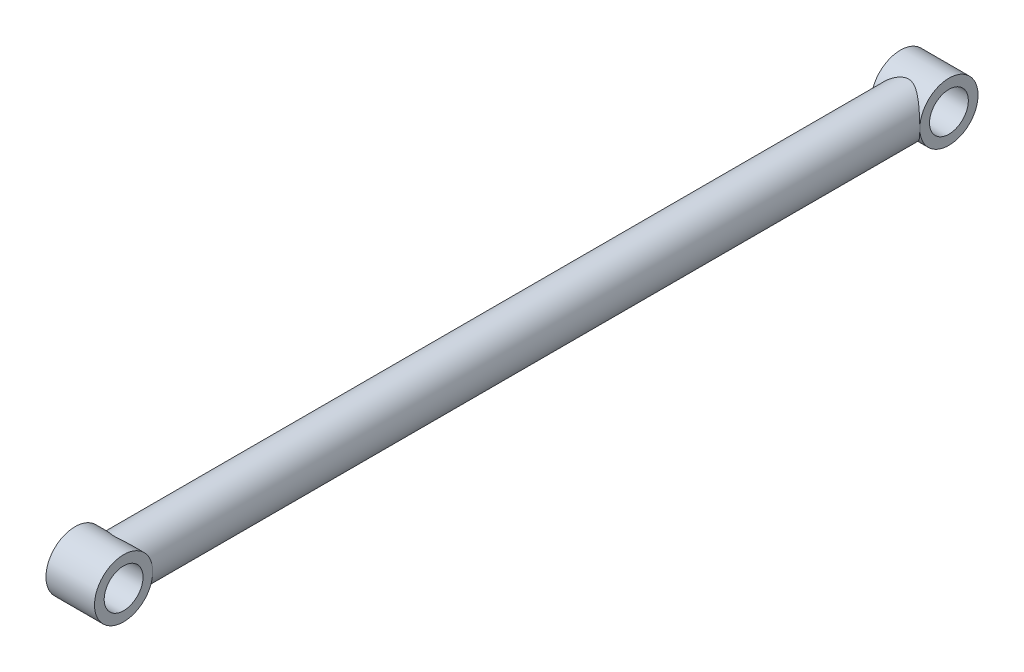
SolidWorks part; units mm, degrees
ref_plane "Front Plane" through (0, 0, 0) normal (0, 0, 1) x (1, 0, 0)
ref_plane "Top Plane" through (0, 0, 0) normal (0, 1, 0) x (1, 0, 0)
ref_plane "Right Plane" through (0, 0, 0) normal (1, 0, 0) x (0, 0, -1)
sketch "Sketch3" plane through (0, 0, 0) normal (0, 0, 1) x (1, 0, 0)
  circle A0 centre (0, 0) radius 5
  dimension "D1" = 10
extrude "Boss-Extrude1" add sketch "Sketch3" along normal blind 170
sketch "Sketch4" plane through (0, 0, 0) normal (1, 0, 0) x (0, 0, -1)
  line L0 (-170, 5) -> (-170, -5) construction
  circle A0 centre (-170, 0) radius 6
  circle A1 centre (0, 0) radius 6
  dimension "D1" = 12
  dimension "D2" = 12
extrude "Boss-Extrude2" add sketch "Sketch4" along normal mid plane 10
sketch "Sketch5" plane through (5, 0, 0) normal (1, 0, 0) x (0, 0, -1)
  circle A0 centre (-170, 0) radius 4
  circle A1 centre (0, 0) radius 3.9999
  dimension "D1" = 8
  dimension "D2" = 7.9999
extrude "Cut-Extrude1" cut sketch "Sketch5" against normal blind 12
